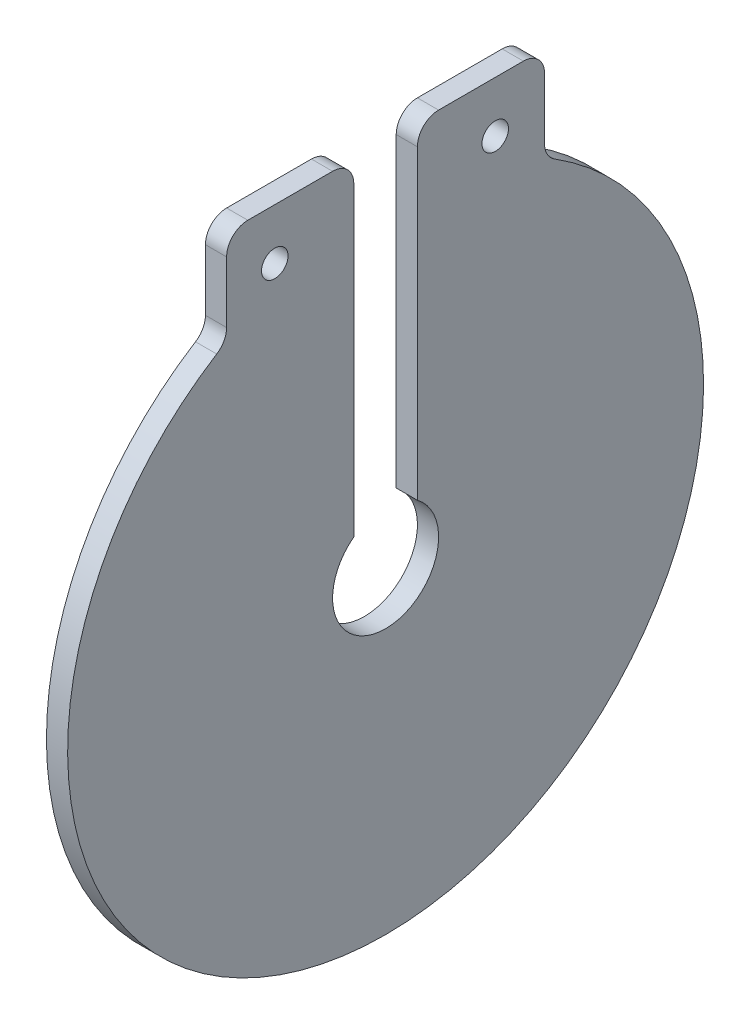
SolidWorks part; units mm, degrees
ref_plane "前视基准面" through (0, 0, 0) normal (0, 0, 1) x (1, 0, 0)
ref_plane "上视基准面" through (0, 0, 0) normal (0, 1, 0) x (1, 0, 0)
ref_plane "右视基准面" through (0, 0, 0) normal (1, 0, 0) x (0, 0, -1)
other "Configuration Table"
sketch "草图1" plane through (0, 0, 0) normal (1, 0, 0) x (0, 0, -1)
  circle A0 centre (0, 0) radius 30
  dimension "D1" = 60
extrude "凸台-拉伸1" add sketch "草图1" along normal blind 2
sketch "草图2" plane through (2, 0, 0) normal (1, 0, 0) x (0, 0, -1)
  line L0 (0, 30) -> (0, -30) construction
  circle A0 centre (0, 0) radius 30 construction
  circle A1 centre (0, 0) radius 5
  dimension "D1" = 10
extrude "切除-拉伸1" cut sketch "草图2" against normal blind 2 contours A1
sketch "草图5" plane through (2, 0, 0) normal (1, 0, 0) x (0, 0, -1)
  line L0 (0, 0) -> (0, 30.1572) construction
  line L2 (-15, 34.8808) -> (15, 34.8808)
  line L3 (-15, 34.8808) -> (-15, 25.9808)
  line L4 (-15, 25.9808) -> (15, 25.9808)
  line L5 (15, 34.8808) -> (15, 25.9808)
  circle A0 centre (0, 0) radius 30 construction
  dimension "D1" = 30
  dimension "D2" = 15
  dimension "D3" = 8.9
extrude "凸台-拉伸2" add sketch "草图5" against normal blind 2
sketch "草图4" plane through (2, 0, 0) normal (1, 0, 0) x (0, 0, -1)
  line L0 (0, 30) -> (0, 0) construction
  line L2 (-3, 38.3727) -> (3, 38.3727)
  line L3 (-3, 38.3727) -> (-3, 1.7509)
  line L4 (-3, 1.7509) -> (3, 1.7509)
  line L5 (3, 38.3727) -> (3, 1.7509)
  circle A0 centre (0, 0) radius 30 construction
  dimension "D1" = 6
  dimension "D2" = 3
extrude "切除-拉伸3" cut sketch "草图4" against normal blind 2
fillet "圆角1" radius 2 6 edges at (1, 34.8808, -15) (1, 34.8808, 15) (1, 25.9808, 15) (1, 25.9808, -15) (1, 34.8808, -3) (1, 34.8808, 3)
sketch "草图6" plane through (2, 0, 0) normal (1, 0, 0) x (0, 0, -1)
  line L0 (0, 0) -> (0, 34.7672) construction
  line L1 (-5, 34.8808) -> (-13, 34.8808) construction
  circle A0 centre (-10.4556, 30.0808) radius 1.25
  circle A1 centre (10.3444, 30.0808) radius 1.25
  dimension "D1" = 2.5
  dimension "D2" = 2.5
  dimension "D3" = 20.8
  dimension "D4" = 4.8
extrude "切除-拉伸4" cut sketch "草图6" against normal blind 2
